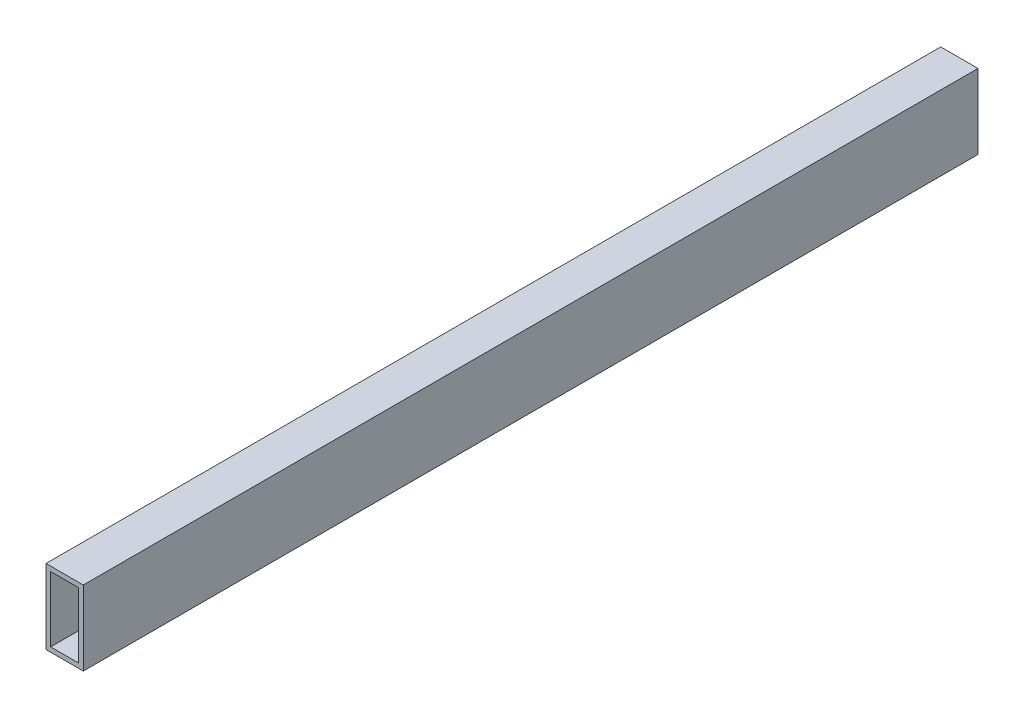
SolidWorks part; units mm, degrees
ref_plane "Front Plane" through (0, 0, 0) normal (0, 0, 1) x (1, 0, 0)
ref_plane "Top Plane" through (0, 0, 0) normal (0, 1, 0) x (1, 0, 0)
ref_plane "Right Plane" through (0, 0, 0) normal (1, 0, 0) x (0, 0, -1)
sketch "Sketch1" plane through (0, 0, 0) normal (0, 0, 1) x (1, 0, 0)
  line L0 (3.175, 47.625) -> (22.225, 47.625)
  line L5 (0, 0) -> (25.4, 0)
  line L6 (0, 0) -> (0, 50.8)
  line L7 (0, 50.8) -> (25.4, 50.8)
  line L8 (25.4, 0) -> (25.4, 50.8)
  line L13 (22.225, 3.175) -> (22.225, 47.625)
  line L14 (3.175, 3.175) -> (22.225, 3.175)
  line L15 (3.175, 3.175) -> (3.175, 47.625)
  dimension "D1" = 25.4
  dimension "D2" = 3.175
  dimension "D3" = 50.8
extrude "Boss-Extrude1" add sketch "Sketch1" along normal blind 609.6
